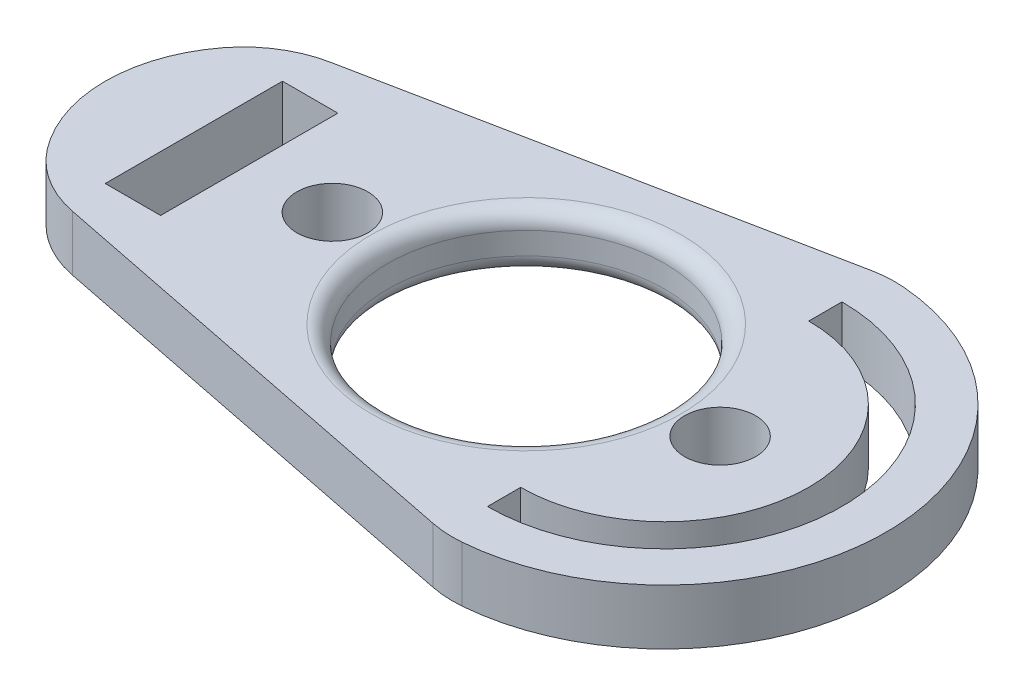
SolidWorks part; units mm, degrees
ref_plane "Front Plane" through (0, 0, 0) normal (0, 0, 1) x (1, 0, 0)
ref_plane "Top Plane" through (0, 0, 0) normal (0, 1, 0) x (1, 0, 0)
ref_plane "Right Plane" through (0, 0, 0) normal (1, 0, 0) x (0, 0, -1)
sketch "Sketch1" plane through (0, 0, 0) normal (0, 1, 0) x (1, 0, 0)
  line L0 (-0.1139, 1.9772) -> (-1.25, 1.7502)
  line L1 (-0.1139, -1.9772) -> (-1.25, -1.7502)
  line L2 (-1.25, 1.25) -> (-1.25, 1.7502)
  line L3 (-1.25, -1.25) -> (-1.25, -1.7502)
  line L4 (-1.25, -1.7502) -> (-4.1832, -1.1642)
  line L5 (-1.25, 1.7502) -> (-4.1832, 1.1642)
  line L6 (-1.25, 1.25) -> (-1.25, 1.05)
  line L7 (-1.25, -1.25) -> (-1.25, -1.05)
  line L8 (0, 1.6) -> (0, 1.3)
  line L9 (0, -1.3) -> (0, -1.6)
  line L17 (-4.25, 0.8) -> (-3.75, 0.8)
  line L18 (-4.25, 0.8) -> (-4.25, -0.8)
  line L19 (-4.25, -0.8) -> (-3.75, -0.8)
  line L20 (-3.75, 0.8) -> (-3.75, -0.8)
  circle A0 centre (-1.25, 0) radius 1.25
  circle A1 centre (-1.25, 0) radius 1.05
  arc A2 (0.1641, 1.9933) -> (0.1641, -1.9933) centre (0, 0) cw
  arc A3 (-0.1139, -1.9772) -> (0.1641, -1.9933) centre (0.0821, -0.9966) ccw
  arc A4 (-4.7783, 0.7954) -> (-4.7783, -0.7954) centre (-3.75, 0) ccw
  arc A5 (0.1641, 1.9933) -> (-0.1139, 1.9772) centre (0.0821, 0.9966) ccw
  arc A6 (-4.1832, 1.1642) -> (-4.7783, 0.7954) centre (-3.9873, 0.1835) ccw
  arc A7 (-4.1832, -1.1642) -> (-4.7783, -0.7954) centre (-3.9873, -0.1835) cw
  circle A8 centre (-3, 0) radius 0.3207
  circle A9 centre (0.5, 0) radius 0.3207
  arc A10 (0, 1.6) -> (0, -1.6) centre (0, 0) cw
  arc A11 (0, 1.3) -> (0, -1.3) centre (0, 0) cw
  point P12 (-3, 0)
  point P20 (0.5, 0)
extrude "Boss-Extrude1" add sketch "Sketch1" along normal blind 0.5 contours A2 A5 L0 L2 A0 L3 L1 A3 A11 L8 A10 L9 A9 | A7 L4 L3 A0 L2 L5 A6 A4 A8 L17 L20 L19 L18
fillet "Fillet3" radius 0.15 2 edges at (-1.25, 0.5, 1.25) (-1.25, 0, 1.25)
